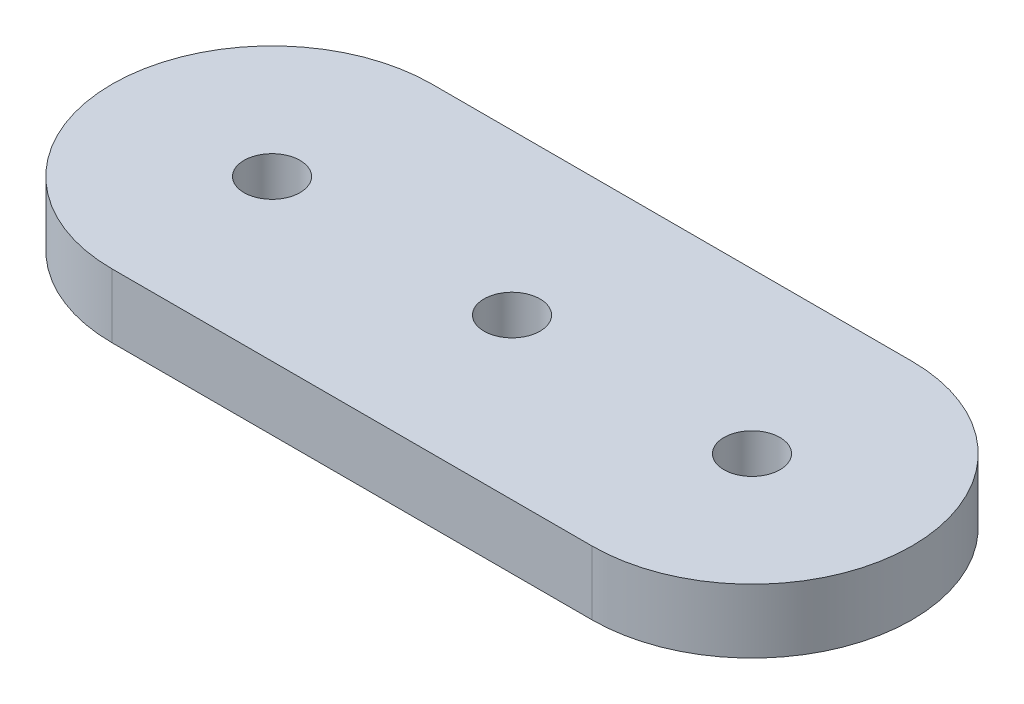
SolidWorks part; units mm, degrees
ref_plane "Спереди" through (0, 0, 0) normal (0, 0, 1) x (1, 0, 0)
ref_plane "Сверху" through (0, 0, 0) normal (0, 1, 0) x (1, 0, 0)
ref_plane "Справа" through (0, 0, 0) normal (1, 0, 0) x (0, 0, -1)
sketch "Эскиз1" plane through (0, 0, 0) normal (0, 1, 0) x (1, 0, 0)
  line L0 (0, 10) -> (30, 10)
  line L1 (0, -10) -> (30, -10)
  line L2 (0, 0) -> (30, 0) construction
  arc A0 (0, 10) -> (0, -10) centre (0, 0) ccw
  arc A1 (30, -10) -> (30, 10) centre (30, 0) ccw
  circle A2 centre (0, 0) radius 1.75
  circle A3 centre (30, 0) radius 1.75
  circle A4 centre (15, 0) radius 1.75
  dimension "D1" = 30
  dimension "D2" = 3.5
  dimension "D3" = 20
extrude "Бобышка-Вытянуть1" add sketch "Эскиз1" along normal blind 4
